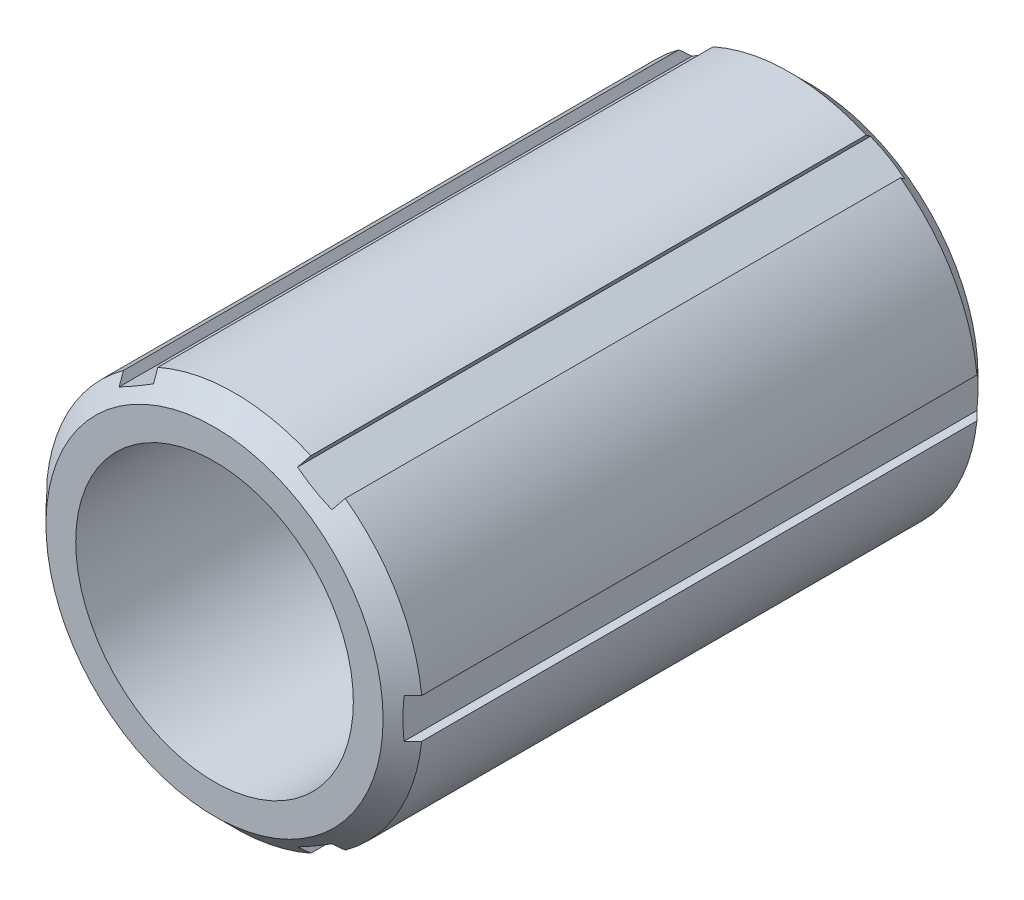
SolidWorks part; units mm, degrees
ref_plane "정면" through (0, 0, 0) normal (0, 0, 1) x (1, 0, 0)
ref_plane "윗면" through (0, 0, 0) normal (0, 1, 0) x (1, 0, 0)
ref_plane "우측면" through (0, 0, 0) normal (1, 0, 0) x (0, 0, -1)
sketch "스케치1" plane through (0, 0, 0) normal (0, 0, 1) x (1, 0, 0)
  circle A0 centre (0, 0) radius 9.5
  circle A1 centre (0, 0) radius 7
  dimension "D1" = 14
  dimension "D2" = 19
extrude "보스-돌출1" add sketch "스케치1" along normal blind 30
chamfer "모따기1" distance 1 angle 45 2 edges at (9.5, 0, 0) (9.5, 0, 30)
sketch "스케치2" plane through (0, 0, 0) normal (0, 0, 1) x (1, 0, 0)
  line L0 (-3.634, 8.2942) -> (-5.366, 7.2942)
  line L1 (-10, 1) -> (-9, 1)
  line L2 (-10, 1) -> (-10, -1)
  line L3 (-10, -1) -> (-9, -1)
  line L4 (-9, 1) -> (-9, -1)
  line L5 (-10, 1) -> (-9, -1) construction
  line L6 (-10, -1) -> (-9, 1) construction
  line L7 (-4.134, 9.1603) -> (-3.634, 8.2942)
  line L8 (-4.134, 9.1603) -> (-5.866, 8.1603)
  line L9 (-5.866, 8.1603) -> (-5.366, 7.2942)
  line L10 (5.366, 7.2942) -> (3.634, 8.2942)
  line L11 (5.866, 8.1603) -> (5.366, 7.2942)
  line L12 (5.866, 8.1603) -> (4.134, 9.1603)
  line L13 (4.134, 9.1603) -> (3.634, 8.2942)
  line L14 (9, -1) -> (9, 1)
  line L15 (10, -1) -> (9, -1)
  line L16 (10, -1) -> (10, 1)
  line L17 (10, 1) -> (9, 1)
  line L18 (3.634, -8.2942) -> (5.366, -7.2942)
  line L19 (4.134, -9.1603) -> (3.634, -8.2942)
  line L20 (4.134, -9.1603) -> (5.866, -8.1603)
  line L21 (5.866, -8.1603) -> (5.366, -7.2942)
  line L22 (-5.366, -7.2942) -> (-3.634, -8.2942)
  line L23 (-5.866, -8.1603) -> (-5.366, -7.2942)
  line L24 (-5.866, -8.1603) -> (-4.134, -9.1603)
  line L25 (-4.134, -9.1603) -> (-3.634, -8.2942)
  circle A0 centre (0, 0) radius 9.5 construction
  point P0 (-9.5, 0)
  point P29 (0, 0)
  dimension "D1" = 2
  dimension "D2" = 1
  dimension "D3" = 6
extrude "컷-돌출1" cut sketch "스케치2" along normal through all
